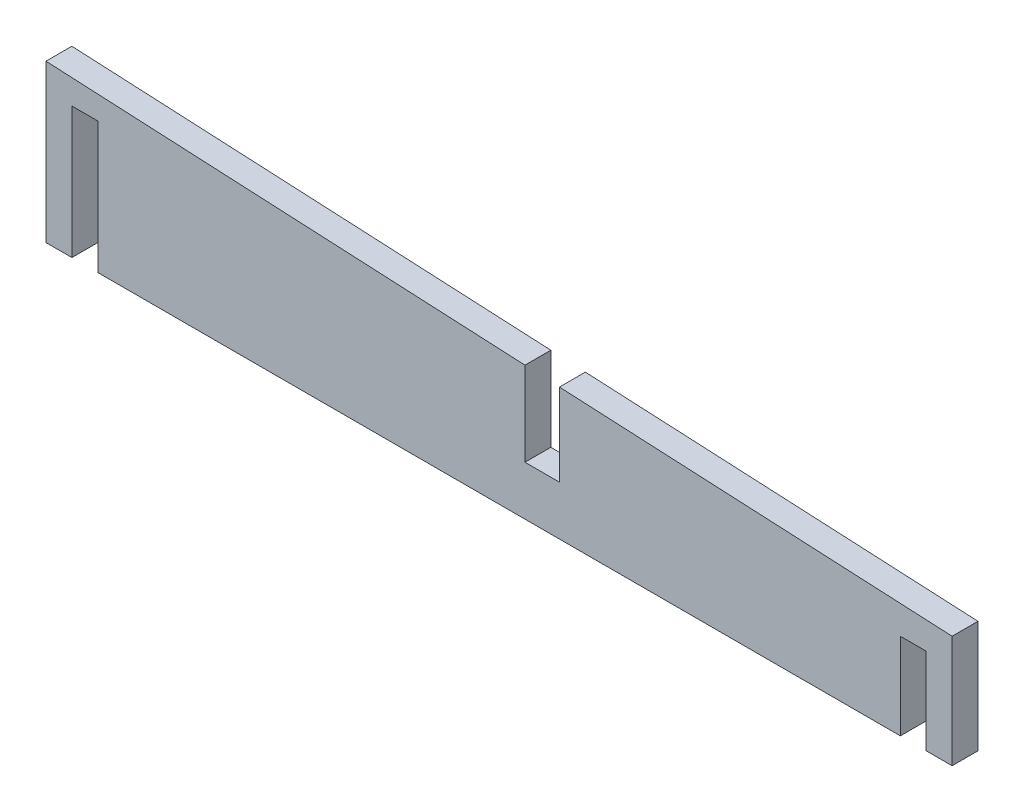
SolidWorks part; units mm, degrees
ref_plane "Front Plane" through (0, 0, 0) normal (0, 0, 1) x (1, 0, 0)
ref_plane "Top Plane" through (0, 0, 0) normal (0, 1, 0) x (1, 0, 0)
ref_plane "Right Plane" through (0, 0, 0) normal (1, 0, 0) x (0, 0, -1)
sketch "Sketch1" plane through (0, 0, 0) normal (0, 0, 1) x (1, 0, 0)
  line L0 (-3, -0.2101) -> (0, -0.2101)
  line L1 (102, -0.2101) -> (102, 12.7899)
  line L3 (102, 12.7899) -> (56.5, 15.0476)
  line L4 (-3, 18) -> (-3, -0.2101)
  line L5 (52.5, 15.2461) -> (52.5, 5.5)
  line L7 (0, 0) -> (0, 15)
  line L8 (0, 15) -> (3, 15)
  line L9 (3, 0) -> (3, 15)
  line L10 (52.5, 5.5) -> (56.5, 5.5)
  line L11 (56.5, 5.5) -> (56.5, 15.0476)
  line L13 (99, 0.7899) -> (99, 9.7899)
  line L14 (99, 9.7899) -> (96, 9.7899)
  line L15 (96, 0.7899) -> (96, 9.7899)
  line L16 (52.5, 15.2461) -> (-3, 18)
  line L17 (0, 0) -> (0, -0.2101)
  line L18 (3, 0) -> (3, -0.2101)
  line L19 (3, -0.2101) -> (96, -0.2101)
  line L20 (96, 0.7899) -> (96, -0.2101)
  line L21 (99, 0.7899) -> (99, -0.2101)
  line L22 (99, -0.2101) -> (102, -0.2101)
  point P4 (0, 0)
  point P9 (1.1318, 2.8401)
  point P19 (96, -0.21)
  point P24 (104.4865, 13.9499)
  point P25 (101.8323, 14.0244)
  point P26 (100.6891, 14.1201)
  point P27 (0, 0)
  point P28 (0, -0.2101)
  dimension "D2" = 3
  dimension "D3" = 3
  dimension "D4" = 3
  dimension "D5" = 15
  dimension "D6" = 3
  dimension "D7" = 9
  dimension "D8" = 93
  dimension "D9" = 3
  dimension "D10" = 3
  dimension "D11" = 1
  dimension "D12" = 4
  dimension "D13" = 49.5
extrude "Boss-Extrude1" add sketch "Sketch1" along normal blind 3
